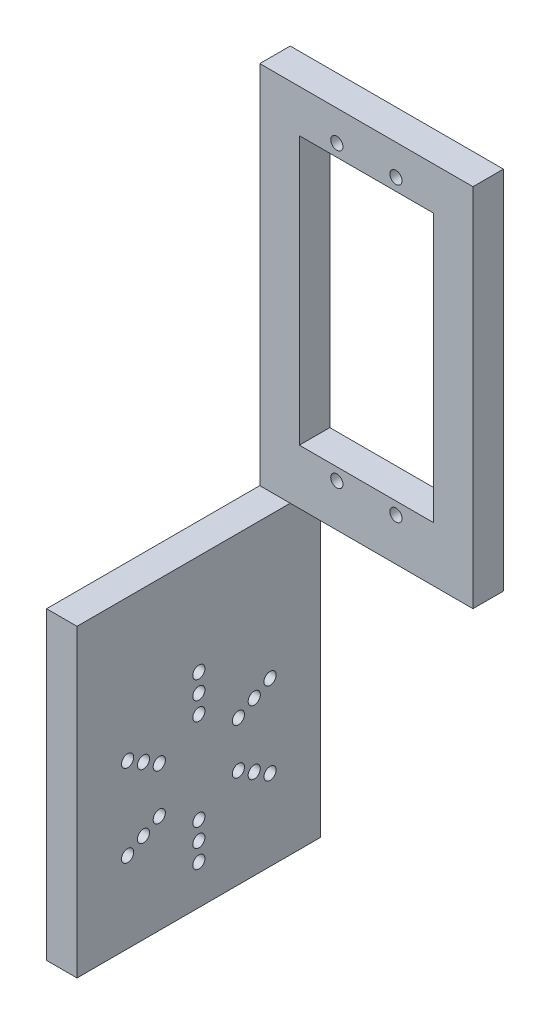
SolidWorks part; units mm, degrees
material "Polylactic Acid"
ref_plane "Front Plane" through (0, 0, 0) normal (0, 0, 1) x (1, 0, 0)
ref_plane "Top Plane" through (0, 0, 0) normal (0, 1, 0) x (1, 0, 0)
ref_plane "Right Plane" through (0, 0, 0) normal (1, 0, 0) x (0, 0, -1)
sketch "Sketch1" plane through (0, 0, 0) normal (0, 0, 1) x (1, 0, 0)
  line L0 (-4.85, -24) -> (4.85, -24) construction
  line L1 (-11, 22) -> (11, 22)
  line L2 (-11, 22) -> (-11, -22)
  line L3 (-11, -22) -> (11, -22)
  line L4 (11, 22) -> (11, -22)
  line L5 (-4.85, -24) -> (-4.85, 24) construction
  line L7 (-17.5, 29) -> (17.5, 29)
  line L8 (-17.5, 29) -> (-17.5, -31)
  line L9 (-17.5, -31) -> (17.5, -31)
  line L10 (17.5, 29) -> (17.5, -31)
  circle A0 centre (-4.85, -24) radius 1
  circle A1 centre (4.85, -24) radius 1
  circle A2 centre (4.85, 24) radius 1
  circle A3 centre (-4.85, 24) radius 1
  point P6 (-4.85, 0)
  point P8 (-11, 0)
  point P17 (0, -24)
  point P18 (0, -22)
  point P23 (0, -31)
  dimension "D7" = 2
  dimension "D1" = 9.7
  dimension "D2" = 48
  dimension "D3" = 22
  dimension "D4" = 44
  dimension "D8" = 35
  dimension "D9" = 60
  dimension "D10" = 7
  dimension "D5" = 2
  dimension "D6" = 2
extrude "Boss-Extrude1" add sketch "Sketch1" along normal blind 5
sketch "Sketch2" plane through (0, 0, 0) normal (0, 0, 1) x (1, 0, 0)
  line L1 (-17.5, -31) -> (-12.5, -31)
  line L2 (-17.5, -31) -> (-17.5, -81)
  line L3 (-17.5, -81) -> (-12.5, -81)
  line L4 (-12.5, -31) -> (-12.5, -81)
  dimension "D1" = 5
  dimension "D2" = 50
extrude "Boss-Extrude2" add sketch "Sketch2" along normal blind 40
sketch "Sketch3" plane through (-12.5, 0, 0) normal (1, 0, 0) x (0, 0, -1)
  line L0 (-20, -74.5) -> (-20, -71.5) construction
  line L1 (-20, -61) -> (-20, -68.5) construction
  line L2 (-40, -81) -> (0, -81) construction
  circle A0 centre (-20, -74.5) radius 1
  circle A1 centre (-20, -71.5) radius 1
  circle A2 centre (-20, -68.5) radius 1
  circle A3 centre (-26.4952, -64.75) radius 1
  circle A4 centre (-29.0933, -66.25) radius 1
  circle A5 centre (-31.6913, -67.75) radius 1
  circle A6 centre (-26.4952, -57.25) radius 1
  circle A7 centre (-29.0933, -55.75) radius 1
  circle A8 centre (-31.6913, -54.25) radius 1
  circle A9 centre (-20, -53.5) radius 1
  circle A10 centre (-20, -50.5) radius 1
  circle A11 centre (-20, -47.5) radius 1
  circle A12 centre (-13.5048, -57.25) radius 1
  circle A13 centre (-10.9067, -55.75) radius 1
  circle A14 centre (-8.3087, -54.25) radius 1
  circle A15 centre (-13.5048, -64.75) radius 1
  circle A16 centre (-10.9067, -66.25) radius 1
  circle A17 centre (-8.3087, -67.75) radius 1
  point P33 (-20, -81)
  point P38 (0, 0)
  dimension "D3" = 2
  dimension "D1" = 3
  dimension "D4" = 7.5
  dimension "D6" = 20
  dimension "D2" = 3
  dimension "D5" = 6
extrude "Cut-Extrude1" cut sketch "Sketch3" against normal up to surface (5 mm away) up to face at (-17.5, -27.6667, 15)
